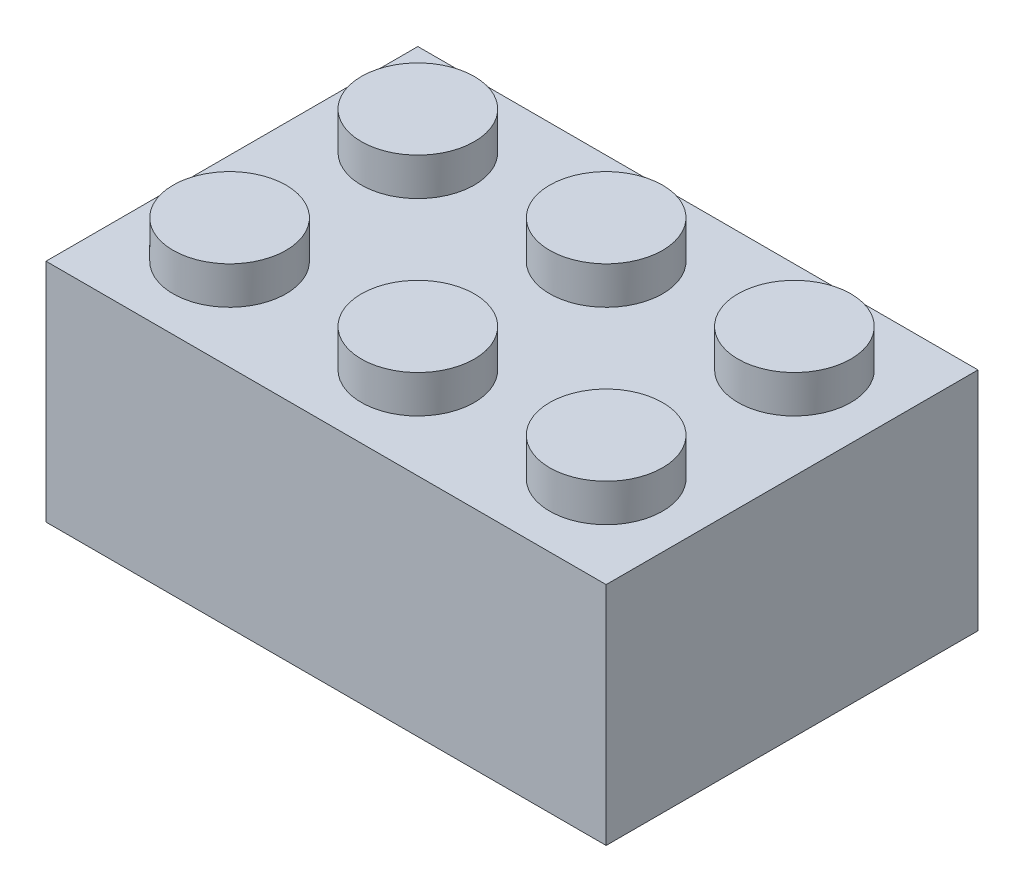
SolidWorks part; units mm, degrees
material "ABS"
ref_plane "Front Plane" through (0, 0, 0) normal (0, 0, 1) x (1, 0, 0)
ref_plane "Top Plane" through (0, 0, 0) normal (0, 1, 0) x (1, 0, 0)
ref_plane "Right Plane" through (0, 0, 0) normal (1, 0, 0) x (0, 0, -1)
sketch "Sketch1" plane through (0, 0, 0) normal (0, 0, 1) x (1, 0, 0)
  line L1 (0, 0) -> (23.8, 0)
  line L2 (0, 0) -> (0, 9.6)
  line L3 (0, 9.6) -> (23.8, 9.6)
  line L4 (23.8, 0) -> (23.8, 9.6)
  dimension "D1" = 23.8
  dimension "D2" = 9.6
extrude "Boss-Extrude1" add sketch "Sketch1" against normal blind 15.8 contours L2 L1 L4 L3
sketch "Sketch2" plane through (0, 9.6, 0) normal (0, 1, 0) x (1, 0, 0)
  line L0 (0, 0) -> (23.8, 0) construction
  line L1 (0, 15.8) -> (0, 0) construction
  circle A0 centre (3.9, 3.9) radius 2.4
  dimension "D1" = 4.8
  dimension "D2" = 3.9
  dimension "D3" = 3.9
extrude "Boss-Extrude2" add sketch "Sketch2" along normal blind 1.6 contours A0
pattern_linear "LPattern1" count 3 spacing 8 along (1, 0, 0) count 2 spacing 8 along (0, 0, -1) of "Boss-Extrude2"
shell "Shell1" thickness 1.2
sketch "Sketch3" plane through (0, 8.4, 0) normal (0, -1, 0) x (1, 0, 0)
  line L0 (0, -15.8) -> (0, 0) construction
  circle A0 centre (7.9, -7.9) radius 3.25
  circle A1 centre (7.9, -7.9) radius 2.4
  dimension "D1" = 4.8
  dimension "D2" = 6.5
  dimension "D3" = 7.9
  dimension "D4" = 7.9
extrude "Boss-Extrude3" add sketch "Sketch3" along normal offset from surface (8.2 mm away) 0.2 up to face at (11.9, 0, -7.9)
pattern_linear "LPattern2" count 2 spacing 8 along (1, 0, 0) of "Boss-Extrude3"
